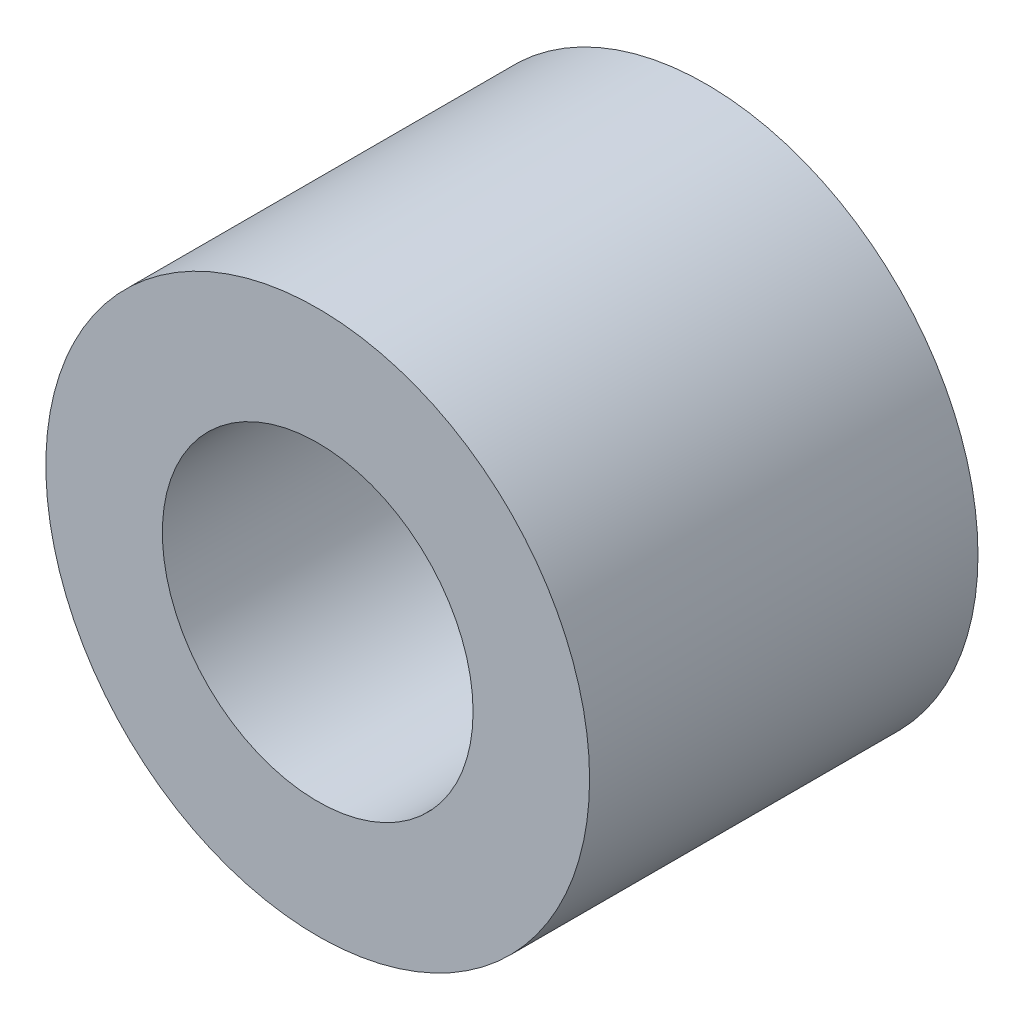
SolidWorks part; units mm, degrees
ref_plane "Plan de face" through (0, 0, 0) normal (0, 0, 1) x (1, 0, 0)
ref_plane "Plan de dessus" through (0, 0, 0) normal (0, 1, 0) x (1, 0, 0)
ref_plane "Plan de droite" through (0, 0, 0) normal (1, 0, 0) x (0, 0, -1)
sketch "Esquisse1" plane through (0, 0, 0) normal (0, 0, 1) x (1, 0, 0)
  circle A0 centre (0, 0) radius 2
  circle A1 centre (0, 0) radius 3.5
  dimension "D1" = 4
  dimension "D2" = 7
extrude "Boss.-Extru.1" add sketch "Esquisse1" along normal blind 5
